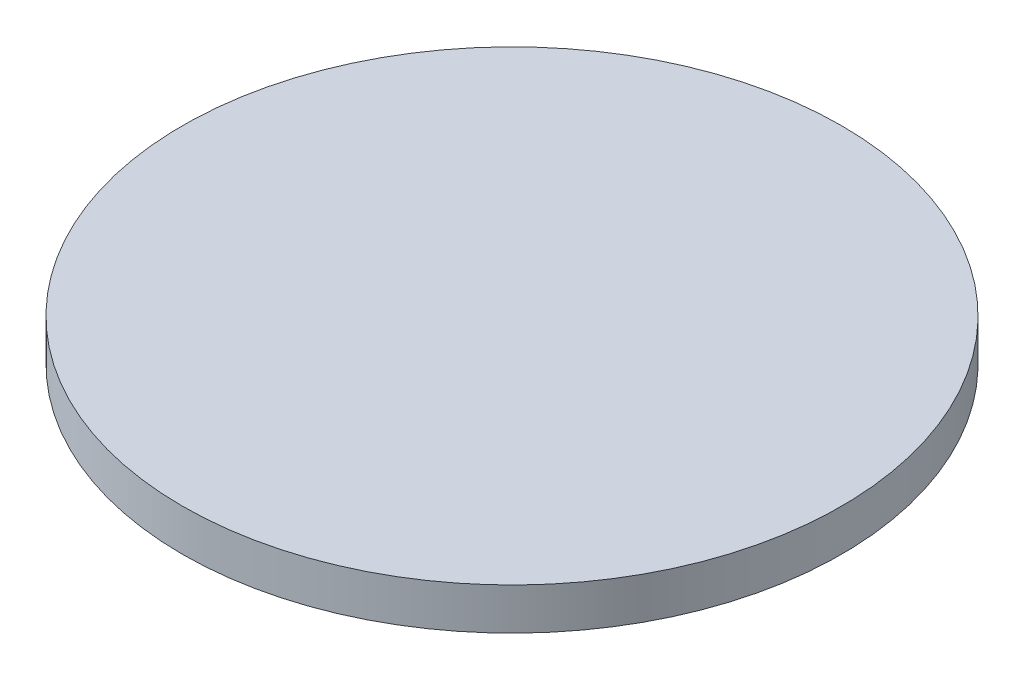
SolidWorks part; units mm, degrees
material "PTFE (general)"
ref_plane "Front Plane" through (0, 0, 0) normal (0, 0, 1) x (1, 0, 0)
ref_plane "Top Plane" through (0, 0, 0) normal (0, 1, 0) x (1, 0, 0)
ref_plane "Right Plane" through (0, 0, 0) normal (1, 0, 0) x (0, 0, -1)
sketch "Sketch1" plane through (0, 0, 0) normal (0, 1, 0) x (1, 0, 0)
  circle A0 centre (0, 0) radius 7.9
  dimension "D1" = 15.8
extrude "Boss-Extrude1" add sketch "Sketch1" along normal blind 1
